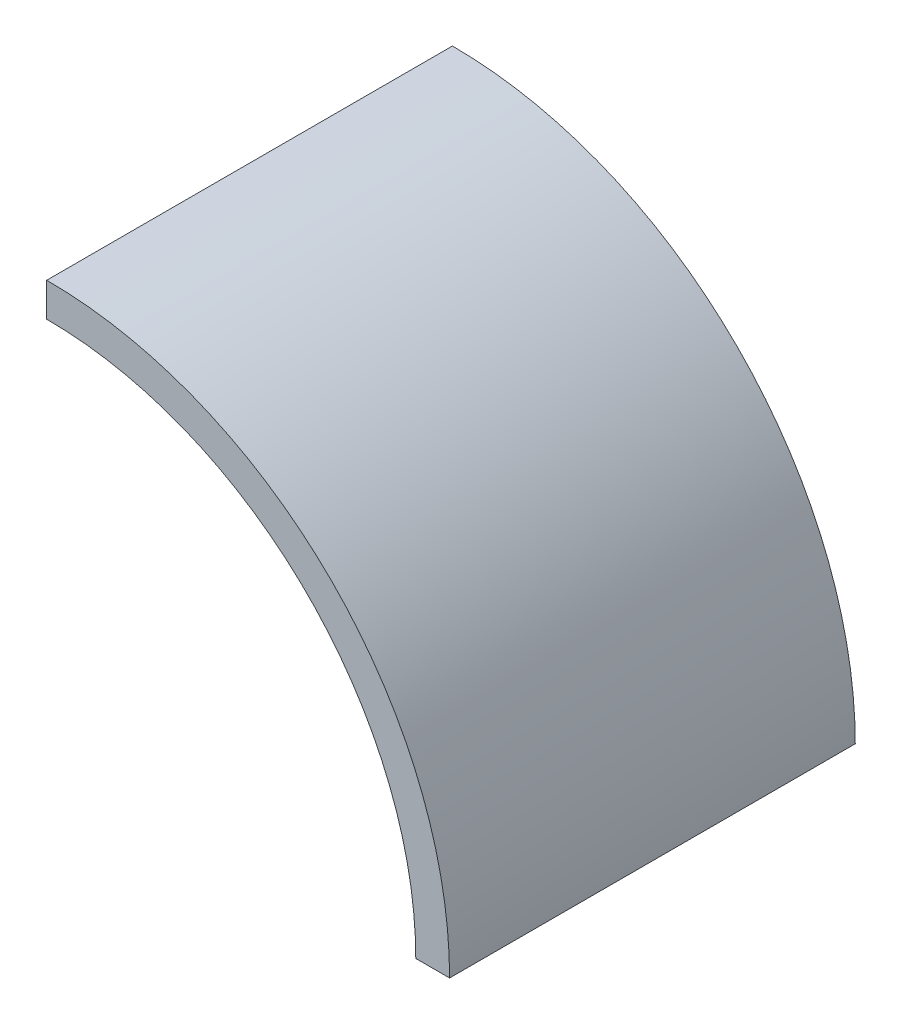
SolidWorks part; units mm, degrees
ref_plane "Ön Düzlem" through (0, 0, 0) normal (0, 0, 1) x (1, 0, 0)
ref_plane "Üst Düzlem" through (0, 0, 0) normal (0, 1, 0) x (1, 0, 0)
ref_plane "Sağ Düzlem" through (0, 0, 0) normal (1, 0, 0) x (0, 0, -1)
sketch "Çizim1" plane through (0, 0, 0) normal (0, 0, 1) x (1, 0, 0)
  line L0 (0, 17.875) -> (0, 16.375)
  line L1 (17.875, 0) -> (16.375, 0)
  line L4 (0, -17.875) -> (0, -16.375) [skipped]
  line L5 (-17.875, 0) -> (-16.375, 0) [skipped]
  arc A0 (17.875, 0) -> (0, 17.875) centre (0, 0) ccw
  arc A1 (16.375, 0) -> (0, 16.375) centre (0, 0) ccw
  point P1 (17.875, 0)
  point P3 (16.375, 0)
  point P6 (0, 0)
  dimension "D1" = 35.75
  dimension "D2" = 32.75
  dimension "D3" = 4
extrude "Yükseklik-Ekstrüzyon1" add sketch "Çizim1" along normal blind 18
